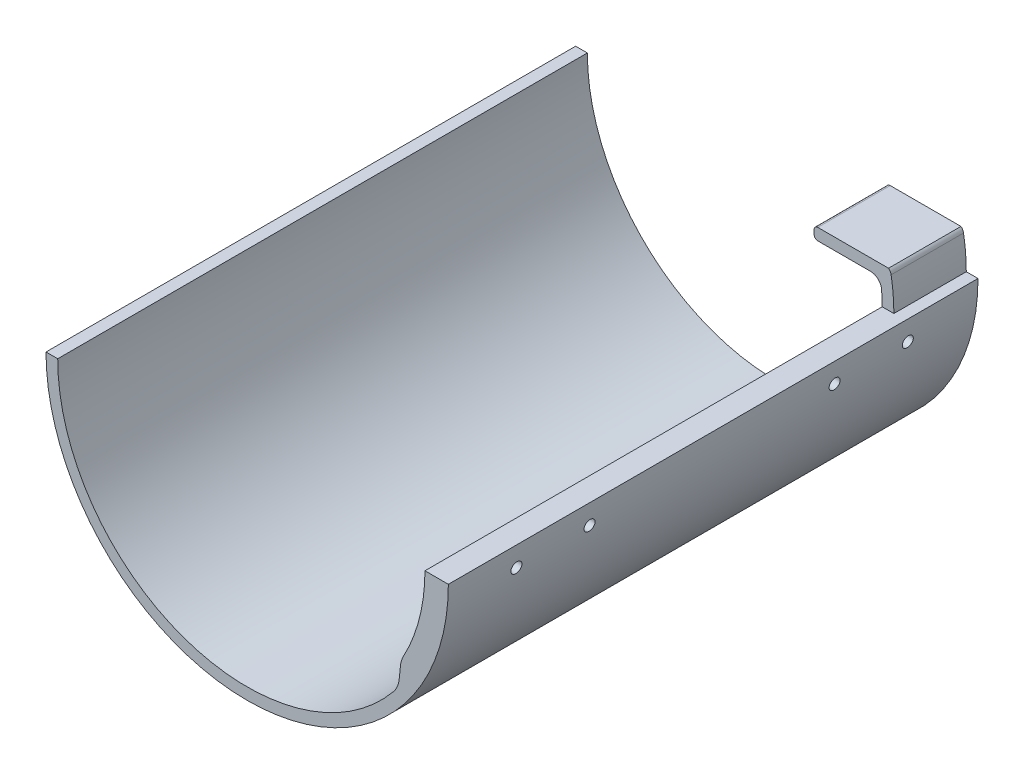
SolidWorks part; units mm, degrees
ref_plane "前视基准面" through (0, 0, 0) normal (0, 0, 1) x (1, 0, 0)
ref_plane "上视基准面" through (0, 0, 0) normal (0, 1, 0) x (1, 0, 0)
ref_plane "右视基准面" through (0, 0, 0) normal (1, 0, 0) x (0, 0, -1)
other "Configuration Table"
sketch "草图1" plane through (0, 0, 0) normal (0, 0, 1) x (1, 0, 0)
  line L0 (-55, 0) -> (-51.8, 0)
  line L1 (51.8, 0) -> (55, 0)
  line L2 (-51.8, 0) -> (51.8, 0) construction
  line L5 (41.9103, -25.796) -> (41.5651, -29.1691)
  line L6 (0, 0) -> (0, 10) construction
  line L7 (0, 10) -> (31, 10) construction
  line L9 (30, 9) -> (30, 7.8)
  line L10 (31, 6.8) -> (45.4414, 6.8)
  line L11 (31, 10) -> (50.344, 10)
  arc A0 (-55, 0) -> (55, 0) centre (0, 0) ccw
  arc A1 (-51.8, 0) -> (40.008, -32.9029) centre (0, 0) ccw
  arc A2 (51.0485, 8.7916) -> (51.8, 0) centre (0, 0) cw
  arc A3 (42.7207, -23.1711) -> (48.431, 4.05) centre (0, 0) ccw
  arc A4 (41.5651, -29.1691) -> (40.008, -32.9029) centre (34.6015, -28.4566) cw
  arc A5 (41.9103, -25.796) -> (42.7207, -23.1711) centre (48.8739, -26.5085) cw
  arc A6 (48.431, 4.05) -> (45.4414, 6.8) centre (45.4414, 3.8) ccw
  arc A7 (51.0485, 8.7916) -> (50.344, 10) centre (49.0775, 8.4521) ccw
  arc A8 (31, 6.8) -> (30, 7.8) centre (31, 7.8) cw
  arc A9 (30, 9) -> (31, 10) centre (31, 9) cw
  point P16 (42.0579, -24.3536)
  point P25 (52.0183, 10)
  point P28 (30, 6.8)
  point P31 (30.5845, 10)
  dimension "D1" = 110
  dimension "D2" = 103.6
  dimension "D3" = 97.2
  dimension "D6" = 7
  dimension "D9" = 3
  dimension "D10" = 2
  dimension "D11" = 1
  dimension "D12" = 1
  dimension "D14" = 51.8
  dimension "D5" = 31
  dimension "D7" = 3.2
  dimension "D8" = 21.4339
  dimension "D13" = 10
extrude "凸台-拉伸1" add sketch "草图1" along normal blind 144.8
sketch "草图4" plane through (0, 0, 144.8) normal (0, 0, 1) x (1, 0, 0)
  line L0 (55, 0) -> (0, 0)
  line L1 (0, 0) -> (50.017, 22.8758)
  arc A0 (55, 0) -> (50.017, 22.8758) centre (0, 0) ccw
sketch "草图5" plane through (0, 0, 0) normal (0, 0, -1) x (-1, 0, 0)
  line L0 (0, 0) -> (0, -5.5)
  line L1 (0, -5.5) -> (54.3615, -5.5)
  line L2 (0, 0) -> (54.3615, -5.5) construction
  line L3 (0, 0) -> (5.5, 54.3615) construction
  line L4 (0, 0) -> (0, 54.639) construction
  line L5 (0, 0) -> (-54.3615, -5.5) construction
  line L6 (0, 0) -> (-5.5, 54.3615) construction
  circle A0 centre (0, 0) radius 54.639
  dimension "D1" = 5.5
  dimension "D2" = 90
ref_plane "基准面1" through (0, 0, 0) normal (-0.9949, 0.1007, 0) x (0.1007, 0.9949, 0)
sketch "草图7" plane through (0, 0, 0) normal (-0.9949, 0.1007, 0) x (0.1007, 0.9949, 0)
  line L0 (-5.5363, -144.8) -> (-5.5363, 0) construction
  line L1 (-55, -144.8) -> (5.5363, -144.8) construction
  line L2 (-0.1363, 0) -> (-0.1363, -144.8) construction
  line L3 (54.639, 0) -> (-54.639, 0) construction
  line L4 (-5.4721, 0) -> (-10.9441, 0) construction
  circle A0 centre (-0.1363, -18.9) radius 1.5
  circle A1 centre (-0.1363, -38.9) radius 1.5
  circle A2 centre (-0.1363, -105.9) radius 1.5
  circle A3 centre (-0.1363, -125.9) radius 1.5
  dimension "D1" = 3
  dimension "D2" = 3
  dimension "D3" = 3
  dimension "D4" = 3
  dimension "D5" = 5.4
  dimension "D6" = 18.9
  dimension "D7" = 20
  dimension "D8" = 18.9
  dimension "D9" = 20
extrude "切除-拉伸6" cut sketch "草图7" against normal blind 80
sketch "草图8" plane through (0, 0, 0) normal (0, 0, -1) x (-1, 0, 0)
  line L0 (-50.017, 22.8758) -> (0, 0)
  line L1 (0, 0) -> (-55, 0)
  arc A0 (-55, 0) -> (-50.017, 22.8758) centre (0, 0) cw
  arc A1 (-50.017, 22.8758) -> (-55, 0) centre (0, 0) ccw construction
extrude "切除-拉伸8" cut sketch "草图4" against normal blind 125
